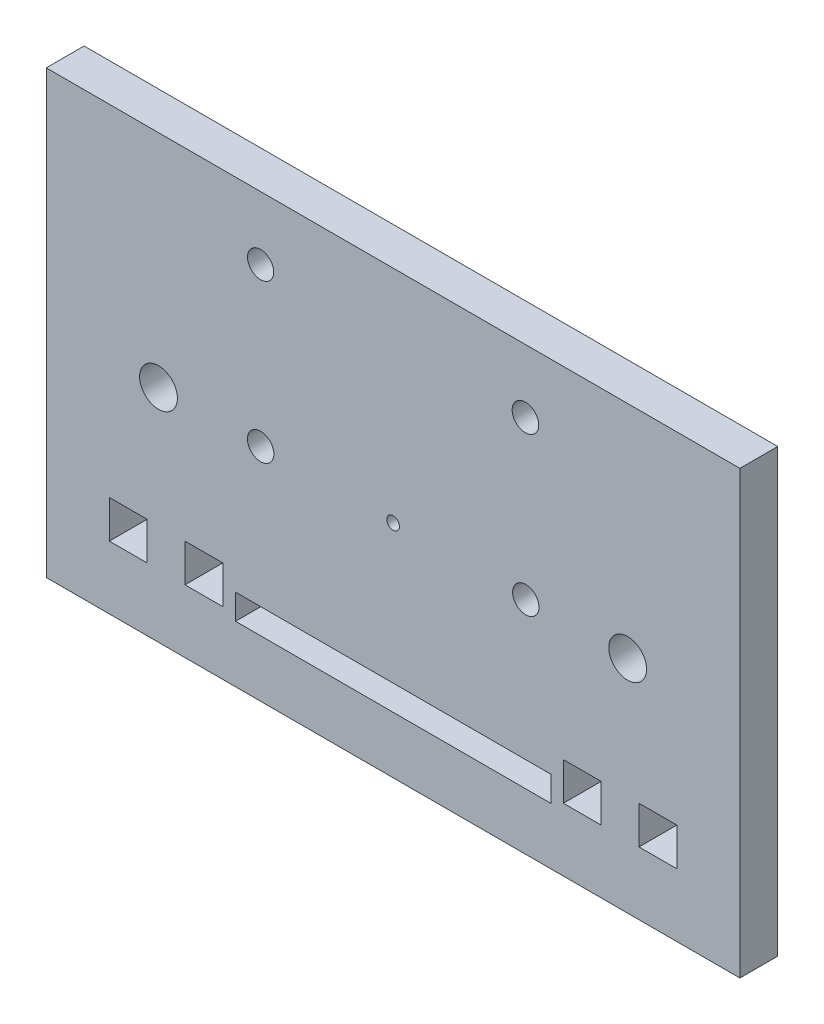
SolidWorks part; units mm, degrees
ref_plane "Front Plane" through (0, 0, 0) normal (0, 0, 1) x (1, 0, 0)
ref_plane "Top Plane" through (0, 0, 0) normal (0, 1, 0) x (1, 0, 0)
ref_plane "Right Plane" through (0, 0, 0) normal (1, 0, 0) x (0, 0, -1)
sketch "Sketch1" plane through (0, 0, 0) normal (0, 0, 1) x (1, 0, 0)
  line L0 (0, 17.5) -> (0, -17.5) construction
  line L1 (-27.5, -17.5) -> (27.5, -17.5)
  line L2 (-27.5, -17.5) -> (-27.5, 17.5)
  line L3 (-27.5, 17.5) -> (27.5, 17.5)
  line L4 (27.5, -17.5) -> (27.5, 17.5)
  line L5 (-27.5, -17.5) -> (27.5, 17.5) construction
  line L6 (-27.5, 17.5) -> (27.5, -17.5) construction
  circle A5 centre (18.6, 0) radius 1.5
  circle A6 centre (-18.6, 0) radius 1.5
  circle A7 centre (0, 0) radius 0.5
  point P14 (0, 0)
  dimension "D1" = 18.6
  dimension "D2" = 1
  dimension "D4" = 3
  dimension "D6" = 55
  dimension "D7" = 35
extrude "Boss-Extrude1" add sketch "Sketch1" along normal blind 3
sketch "Sketch2" plane through (0, 0, 3) normal (0, 0, 1) x (1, 0, 0)
  line L1 (-12.4916, -11) -> (12.5084, -11)
  line L2 (-12.4916, -11) -> (-12.4916, -13)
  line L3 (-12.4916, -13) -> (12.5084, -13)
  line L4 (12.5084, -11) -> (12.5084, -13)
  line L5 (-12.5, -9.5) -> (12.5, -9.5) construction
  dimension "D1" = 2
  dimension "D2" = 25
  dimension "D3" = 1.5
extrude "Cut-Extrude1" cut sketch "Sketch2" against normal blind 4
sketch "Sketch3" plane through (0, 0, 3) normal (0, 0, 1) x (1, 0, 0)
  line L0 (0, -9.5) -> (0, -11) construction
  line L1 (-12.5, -9.5) -> (12.5, -9.5) construction
  line L2 (13.5, -9.5) -> (13.5, -12.5)
  line L4 (-22.5, -12.5) -> (-22.5, -9.5)
  line L7 (16.5, -12.5) -> (13.5, -12.5)
  line L8 (16.5, -9.5) -> (16.5, -12.5)
  line L9 (-22.5, -9.5) -> (-19.5, -9.5)
  line L10 (-22.5, -9.5) -> (-22.5, -12.5)
  line L11 (-22.5, -12.5) -> (-19.5, -12.5)
  line L12 (-19.5, -9.5) -> (-19.5, -12.5)
  line L13 (-16.5, -9.5) -> (-13.5, -9.5)
  line L14 (-16.5, -9.5) -> (-16.5, -12.5)
  line L15 (-16.5, -12.5) -> (-13.5, -12.5)
  line L16 (-13.5, -9.5) -> (-13.5, -12.5)
  line L17 (16.5, -9.5) -> (13.5, -9.5)
  line L18 (19.5, -9.5) -> (19.5, -12.5)
  line L19 (22.5, -12.5) -> (19.5, -12.5)
  line L20 (22.5, -9.5) -> (22.5, -12.5)
  line L21 (22.5, -9.5) -> (19.5, -9.5)
  line L22 (22.5, -12.5) -> (22.5, -9.5)
  dimension "D1" = 1.5
  dimension "D2" = 3
  dimension "D4" = 3
  dimension "D5" = 3
extrude "Cut-Extrude2" cut sketch "Sketch3" against normal blind 3 contours L12 L9 L4 L11 | L16 L13 L14 L15 | L8 L17 L2 L7 | L20 L21 L18 L19
sketch "Sketch4" plane through (0, 0, 3) normal (0, 0, 1) x (1, 0, 0)
  line L0 (0, 4.0413) -> (0, -2.75) construction
  circle A0 centre (-10.5023, -0.0026) radius 1.0478
  circle A1 centre (10.524, -0.0093) radius 1.0448
extrude "Cut-Extrude3" cut sketch "Sketch4" against normal blind 3
sketch "Sketch5" plane through (0, 0, 3) normal (0, 0, 1) x (1, 0, 0)
  circle A0 centre (-10.5042, 12.486) radius 1.038
  circle A1 centre (10.4942, 12.4884) radius 1.0525
extrude "Cut-Extrude4" cut sketch "Sketch5" against normal blind 3
